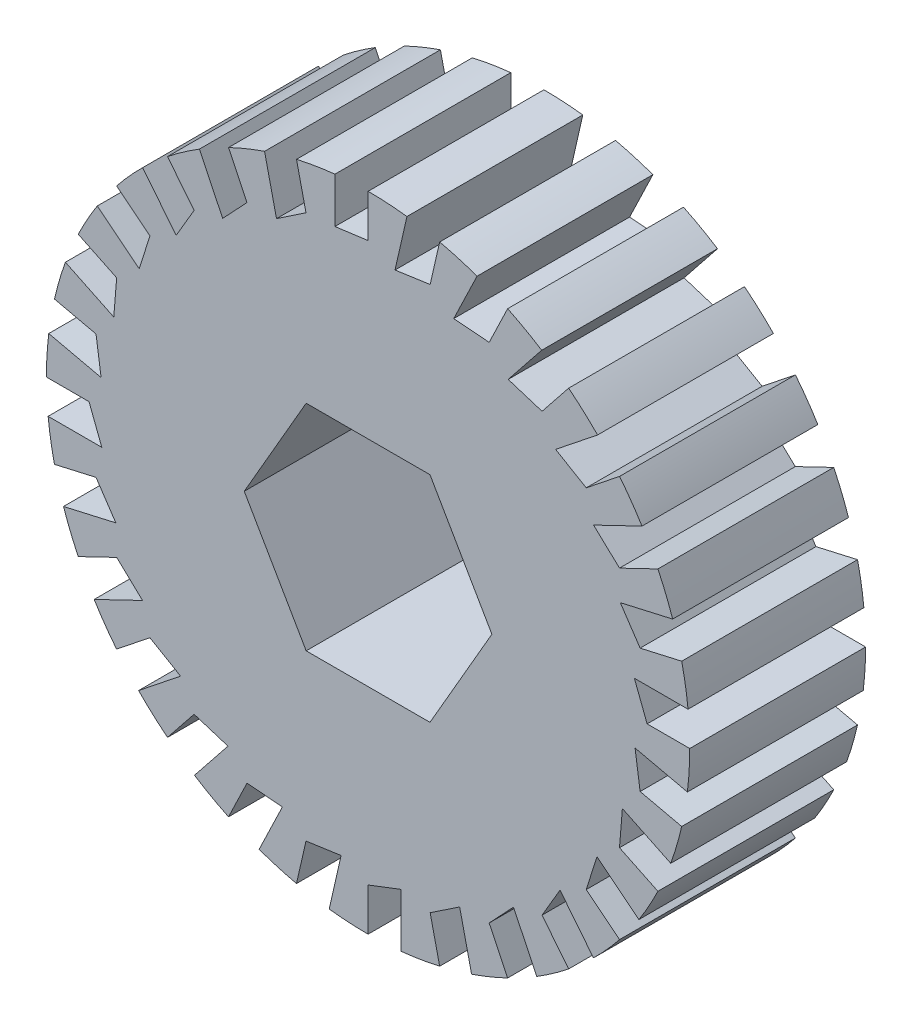
SolidWorks part; units mm, degrees
ref_plane "Front Plane" through (0, 0, 0) normal (0, 0, 1) x (1, 0, 0)
ref_plane "Top Plane" through (0, 0, 0) normal (0, 1, 0) x (1, 0, 0)
ref_plane "Right Plane" through (0, 0, 0) normal (1, 0, 0) x (0, 0, -1)
sketch "Sketch1" plane through (0, 0, 0) normal (0, 0, 1) x (1, 0, 0)
  circle A0 centre (0, 0) radius 19.05
  dimension "D1" = 38.1
extrude "Boss-Extrude1" add sketch "Sketch1" along normal blind 10.414
sketch "Sketch2" plane through (0, 0, 10.414) normal (0, 0, 1) x (1, 0, 0)
  line L1 (-7.3323, 0) -> (-3.6662, -6.35)
  line L2 (-3.6662, -6.35) -> (3.6662, -6.35)
  line L3 (3.6662, -6.35) -> (7.3323, 0)
  line L4 (7.3323, 0) -> (3.6662, 6.35)
  line L5 (3.6662, 6.35) -> (-3.6662, 6.35)
  line L6 (-3.6662, 6.35) -> (-7.3323, 0)
  circle A0 centre (0, 0) radius 6.35 construction
  dimension "D1" = 12.7
extrude "Cut-Extrude1" cut sketch "Sketch2" against normal up to surface (10.414 mm away) up to face at (19.05, 0, 0)
sketch "Sketch3" plane through (0, 0, 10.414) normal (0, 0, 1) x (1, 0, 0)
  line L0 (0, 19.05) -> (0, 16.5252)
  line L1 (0, 16.5252) -> (-1.9632, 16.2626)
  line L2 (-1.9632, 16.2626) -> (-1.9632, 18.9486)
  line L3 (3.6772, 16.1109) -> (1.5952, 15.8114)
  line L4 (4.239, 18.5724) -> (3.6772, 16.1109)
  line L5 (1.5952, 15.8114) -> (2.3025, 18.9103)
  line L6 (7.17, 14.8887) -> (5.0736, 15.06)
  line L7 (8.2655, 17.1635) -> (7.17, 14.8887)
  line L8 (5.0736, 15.06) -> (6.4527, 17.9239)
  line L9 (10.3033, 12.9199) -> (8.2975, 13.5535)
  line L10 (11.8775, 14.8939) -> (10.3033, 12.9199)
  line L11 (8.2975, 13.5535) -> (10.2794, 16.0386)
  line L12 (12.9199, 10.3033) -> (11.1054, 11.3673)
  line L13 (14.8939, 11.8775) -> (12.9199, 10.3033)
  line L14 (11.1054, 11.3673) -> (13.5906, 13.3491)
  line L15 (14.8887, 7.17) -> (13.3564, 8.6111)
  line L16 (17.1635, 8.2655) -> (14.8887, 7.17)
  line L17 (13.3564, 8.6111) -> (16.2203, 9.9902)
  line L18 (16.1109, 3.6772) -> (14.9377, 5.4231)
  line L19 (18.5724, 4.239) -> (16.1109, 3.6772)
  line L20 (14.9377, 5.4231) -> (18.0366, 6.1304)
  line L21 (16.5252, 0) -> (15.77, 1.9632)
  line L22 (19.05, 0) -> (16.5252, 0)
  line L23 (15.77, 1.9632) -> (18.9486, 1.9632)
  line L24 (16.1109, -3.6772) -> (15.8114, -1.5952)
  line L25 (18.5724, -4.239) -> (16.1109, -3.6772)
  line L26 (15.8114, -1.5952) -> (18.9103, -2.3025)
  line L27 (14.8887, -7.17) -> (15.06, -5.0736)
  line L28 (17.1635, -8.2655) -> (14.8887, -7.17)
  line L29 (15.06, -5.0736) -> (17.9239, -6.4527)
  line L30 (12.9199, -10.3033) -> (13.5535, -8.2975)
  line L31 (14.8939, -11.8775) -> (12.9199, -10.3033)
  line L32 (13.5535, -8.2975) -> (16.0386, -10.2794)
  line L33 (10.3033, -12.9199) -> (11.3673, -11.1054)
  line L34 (11.8775, -14.8939) -> (10.3033, -12.9199)
  line L35 (11.3673, -11.1054) -> (13.3491, -13.5906)
  line L36 (7.17, -14.8887) -> (8.6111, -13.3564)
  line L37 (8.2655, -17.1635) -> (7.17, -14.8887)
  line L38 (8.6111, -13.3564) -> (9.9902, -16.2203)
  line L39 (3.6772, -16.1109) -> (5.4231, -14.9377)
  line L40 (4.239, -18.5724) -> (3.6772, -16.1109)
  line L41 (5.4231, -14.9377) -> (6.1304, -18.0366)
  line L42 (0, -16.5252) -> (1.9632, -15.77)
  line L43 (0, -19.05) -> (0, -16.5252)
  line L44 (1.9632, -15.77) -> (1.9632, -18.9486)
  line L45 (-3.6772, -16.1109) -> (-1.5952, -15.8114)
  line L46 (-4.239, -18.5724) -> (-3.6772, -16.1109)
  line L47 (-1.5952, -15.8114) -> (-2.3025, -18.9103)
  line L48 (-7.17, -14.8887) -> (-5.0736, -15.06)
  line L49 (-8.2655, -17.1635) -> (-7.17, -14.8887)
  line L50 (-5.0736, -15.06) -> (-6.4527, -17.9239)
  line L51 (-10.3033, -12.9199) -> (-8.2975, -13.5535)
  line L52 (-11.8775, -14.8939) -> (-10.3033, -12.9199)
  line L53 (-8.2975, -13.5535) -> (-10.2794, -16.0386)
  line L54 (-12.9199, -10.3033) -> (-11.1054, -11.3673)
  line L55 (-14.8939, -11.8775) -> (-12.9199, -10.3033)
  line L56 (-11.1054, -11.3673) -> (-13.5906, -13.3491)
  line L57 (-14.8887, -7.17) -> (-13.3564, -8.6111)
  line L58 (-17.1635, -8.2655) -> (-14.8887, -7.17)
  line L59 (-13.3564, -8.6111) -> (-16.2203, -9.9902)
  line L60 (-16.1109, -3.6772) -> (-14.9377, -5.4231)
  line L61 (-18.5724, -4.239) -> (-16.1109, -3.6772)
  line L62 (-14.9377, -5.4231) -> (-18.0366, -6.1304)
  line L63 (-16.5252, 0) -> (-15.77, -1.9632)
  line L64 (-19.05, 0) -> (-16.5252, 0)
  line L65 (-15.77, -1.9632) -> (-18.9486, -1.9632)
  line L66 (-16.1109, 3.6772) -> (-15.8114, 1.5952)
  line L67 (-18.5724, 4.239) -> (-16.1109, 3.6772)
  line L68 (-15.8114, 1.5952) -> (-18.9103, 2.3025)
  line L69 (-14.8887, 7.17) -> (-15.06, 5.0736)
  line L70 (-17.1635, 8.2655) -> (-14.8887, 7.17)
  line L71 (-15.06, 5.0736) -> (-17.9239, 6.4527)
  line L72 (-12.9199, 10.3033) -> (-13.5535, 8.2975)
  line L73 (-14.8939, 11.8775) -> (-12.9199, 10.3033)
  line L74 (-13.5535, 8.2975) -> (-16.0386, 10.2794)
  line L75 (-10.3033, 12.9199) -> (-11.3673, 11.1054)
  line L76 (-11.8775, 14.8939) -> (-10.3033, 12.9199)
  line L77 (-11.3673, 11.1054) -> (-13.3491, 13.5906)
  line L78 (-7.17, 14.8887) -> (-8.6111, 13.3564)
  line L79 (-8.2655, 17.1635) -> (-7.17, 14.8887)
  line L80 (-8.6111, 13.3564) -> (-9.9902, 16.2203)
  line L81 (-3.6772, 16.1109) -> (-5.4231, 14.9377)
  line L82 (-4.239, 18.5724) -> (-3.6772, 16.1109)
  line L83 (-5.4231, 14.9377) -> (-6.1304, 18.0366)
  arc A0 (0, 19.05) -> (-1.9632, 18.9486) centre (0, 0) ccw
  arc A1 (4.239, 18.5724) -> (2.3025, 18.9103) centre (0, 0) ccw
  arc A2 (8.2655, 17.1635) -> (6.4527, 17.9239) centre (0, 0) ccw
  arc A3 (11.8775, 14.8939) -> (10.2794, 16.0386) centre (0, 0) ccw
  arc A4 (14.8939, 11.8775) -> (13.5906, 13.3491) centre (0, 0) ccw
  arc A5 (17.1635, 8.2655) -> (16.2203, 9.9902) centre (0, 0) ccw
  arc A6 (18.5724, 4.239) -> (18.0366, 6.1304) centre (0, 0) ccw
  arc A7 (19.05, 0) -> (18.9486, 1.9632) centre (0, 0) ccw
  arc A8 (18.5724, -4.239) -> (18.9103, -2.3025) centre (0, 0) ccw
  arc A9 (17.1635, -8.2655) -> (17.9239, -6.4527) centre (0, 0) ccw
  arc A10 (14.8939, -11.8775) -> (16.0386, -10.2794) centre (0, 0) ccw
  arc A11 (11.8775, -14.8939) -> (13.3491, -13.5906) centre (0, 0) ccw
  arc A12 (8.2655, -17.1635) -> (9.9902, -16.2203) centre (0, 0) ccw
  arc A13 (4.239, -18.5724) -> (6.1304, -18.0366) centre (0, 0) ccw
  arc A14 (0, -19.05) -> (1.9632, -18.9486) centre (0, 0) ccw
  arc A15 (-4.239, -18.5724) -> (-2.3025, -18.9103) centre (0, 0) ccw
  arc A16 (-8.2655, -17.1635) -> (-6.4527, -17.9239) centre (0, 0) ccw
  arc A17 (-11.8775, -14.8939) -> (-10.2794, -16.0386) centre (0, 0) ccw
  arc A18 (-14.8939, -11.8775) -> (-13.5906, -13.3491) centre (0, 0) ccw
  arc A19 (-17.1635, -8.2655) -> (-16.2203, -9.9902) centre (0, 0) ccw
  arc A20 (-18.5724, -4.239) -> (-18.0366, -6.1304) centre (0, 0) ccw
  arc A21 (-19.05, 0) -> (-18.9486, -1.9632) centre (0, 0) ccw
  arc A22 (-18.5724, 4.239) -> (-18.9103, 2.3025) centre (0, 0) ccw
  arc A23 (-17.1635, 8.2655) -> (-17.9239, 6.4527) centre (0, 0) ccw
  arc A24 (-14.8939, 11.8775) -> (-16.0386, 10.2794) centre (0, 0) ccw
  arc A25 (-11.8775, 14.8939) -> (-13.3491, 13.5906) centre (0, 0) ccw
  arc A26 (-8.2655, 17.1635) -> (-9.9902, 16.2203) centre (0, 0) ccw
  arc A27 (-4.239, 18.5724) -> (-6.1304, 18.0366) centre (0, 0) ccw
  point P117 (0, 0)
  dimension "D1" = 28
extrude "Cut-Extrude2" cut sketch "Sketch3" against normal blind 127
